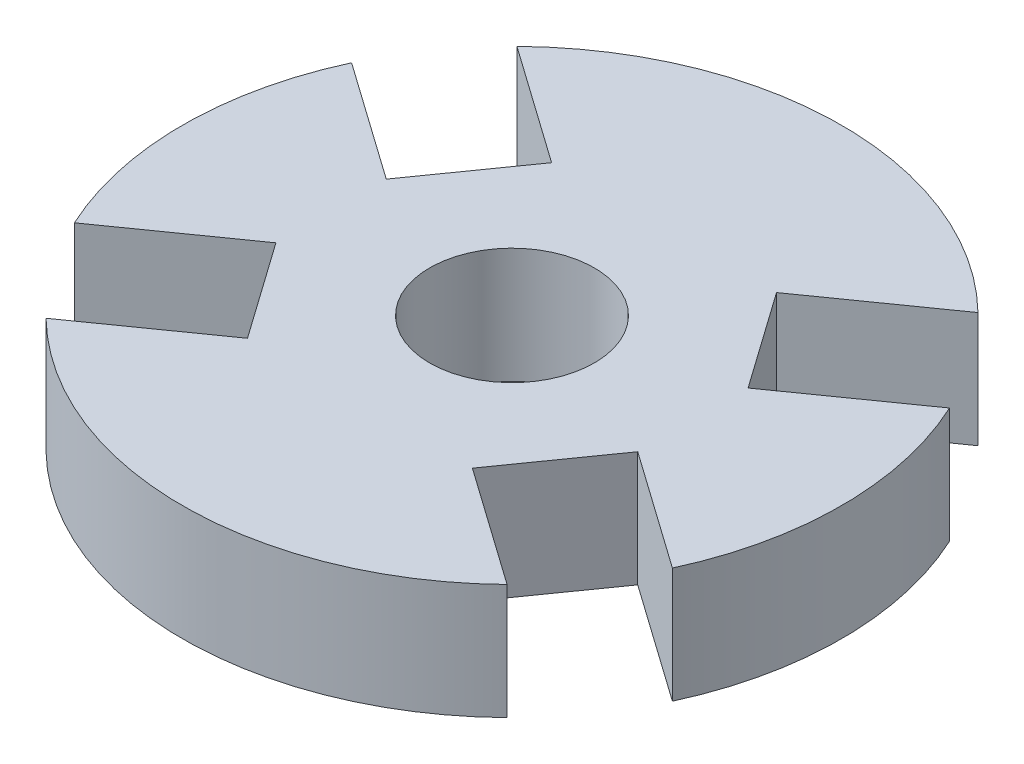
SolidWorks part; units mm, degrees
ref_plane "Alzado" through (0, 0, 0) normal (0, 0, 1) x (1, 0, 0)
ref_plane "Planta" through (0, 0, 0) normal (0, 1, 0) x (1, 0, 0)
ref_plane "Vista lateral" through (0, 0, 0) normal (1, 0, 0) x (0, 0, -1)
sketch "Croquis1" plane through (0, 0, 0) normal (0, 1, 0) x (1, 0, 0)
  circle A0 centre (0, 0) radius 10
  circle A1 centre (0, 0) radius 2.5
  dimension "D1" = 20
  dimension "D2" = 5
extrude "Saliente-Extruir1" add sketch "Croquis1" along normal blind 3.5
sketch "Croquis3" plane through (0, 3.5, 0) normal (0, 1, 0) x (1, 0, 0)
  line L0 (0, 0) -> (0, 10) construction
  line L1 (0, 0) -> (10, 0) construction
  line L2 (0, 0) -> (8.1677, 5.7696) construction
  line L8 (12.9226, 6.9246) -> (5.4899, 1.6742)
  line L9 (12.9226, 6.9246) -> (10.8455, 9.8649)
  line L10 (10.8455, 9.8649) -> (3.4129, 4.6146)
  line L11 (5.4899, 1.6742) -> (3.4129, 4.6146)
  line L12 (12.9226, 6.9246) -> (3.4129, 4.6146) construction
  line L13 (10.8455, 9.8649) -> (5.4899, 1.6742) construction
  line L15 (-12.9226, -6.9246) -> (-3.4129, -4.6146) construction
  line L16 (-10.8455, -9.8649) -> (-5.4899, -1.6742) construction
  line L17 (-3.4129, -4.6146) -> (-5.4899, -1.6742)
  line L18 (-12.9226, -6.9246) -> (-5.4899, -1.6742)
  line L19 (-10.8455, -9.8649) -> (-12.9226, -6.9246)
  line L20 (-10.8455, -9.8649) -> (-3.4129, -4.6146)
  line L21 (10.8455, -9.8649) -> (5.4899, -1.6742) construction
  line L22 (12.9226, -6.9246) -> (3.4129, -4.6146) construction
  line L23 (-10.8455, 9.8649) -> (-5.4899, 1.6742) construction
  line L24 (-12.9226, 6.9246) -> (-3.4129, 4.6146) construction
  line L25 (10.8455, -9.8649) -> (3.4129, -4.6146)
  line L26 (10.8455, -9.8649) -> (12.9226, -6.9246)
  line L27 (12.9226, -6.9246) -> (5.4899, -1.6742)
  line L28 (3.4129, -4.6146) -> (5.4899, -1.6742)
  line L29 (-5.4899, 1.6742) -> (-3.4129, 4.6146)
  line L30 (-10.8455, 9.8649) -> (-3.4129, 4.6146)
  line L31 (-12.9226, 6.9246) -> (-10.8455, 9.8649)
  line L32 (-12.9226, 6.9246) -> (-5.4899, 1.6742)
  circle A0 centre (0, 0) radius 10 construction
  dimension "D2" = 9.1
  dimension "D3" = 3.6
  dimension "D1" = 35.237
extrude "Cortar-Extruir1" cut sketch "Croquis3" against normal blind 3.5
equation "\"dface\"= 60"
equation "\"joind\"=9"
equation "\"P\"=1/3"
equation "\"thickness\"=3.5"
equation "\"D1@Croquis1\" = \"P\" * \"dface\""
equation "\"D1@Saliente-Extruir1\"=\"thickness\""
equation "\"D2@Croquis3\"=\"joind\"+\"clear\""
equation "\"D3@Croquis3\"=\"thickness\"+\"clear\""
equation "\"clear\"=.1"
equation "\"D2@Croquis1\"=( \"P\" * \"dface\" ) - 4 * \"joind\""
equation "\"D1@Cortar-Extruir1\"=\"thickness\""
